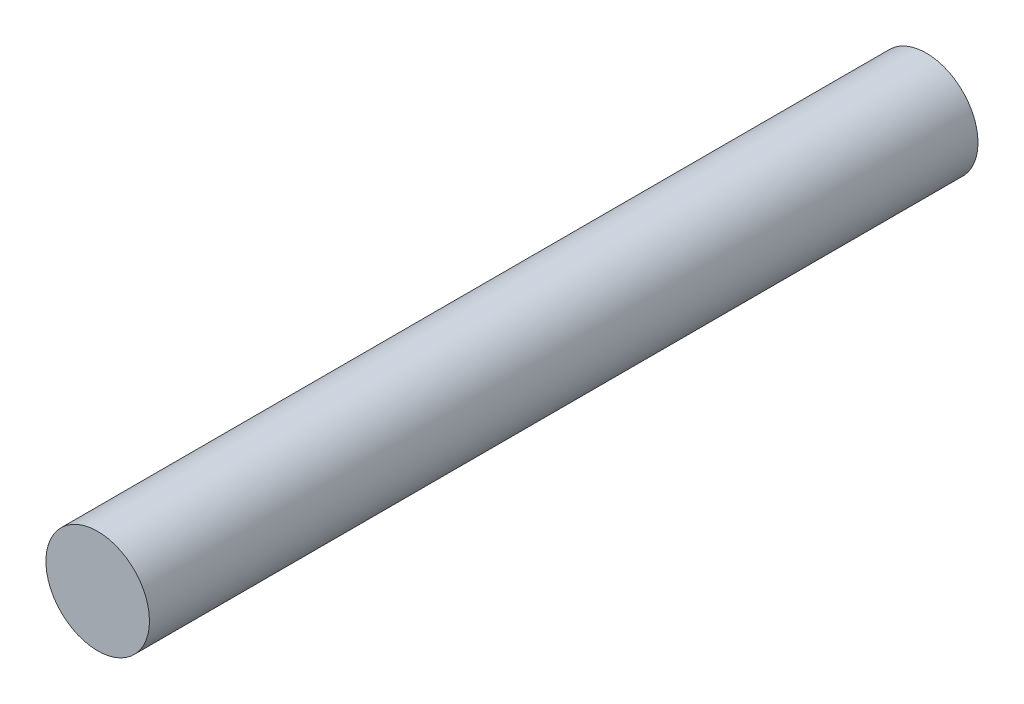
SolidWorks part; units mm, degrees
ref_plane "Front Plane" through (0, 0, 0) normal (0, 0, 1) x (1, 0, 0)
ref_plane "Top Plane" through (0, 0, 0) normal (0, 1, 0) x (1, 0, 0)
ref_plane "Right Plane" through (0, 0, 0) normal (1, 0, 0) x (0, 0, -1)
sketch "Sketch3" plane through (0, 0, 0) normal (0, 0, 1) x (1, 0, 0)
  circle A0 centre (0, 0) radius 1.5875
  dimension "D1" = 3.175
extrude "Boss-Extrude1" add sketch "Sketch3" along normal blind 25.4
